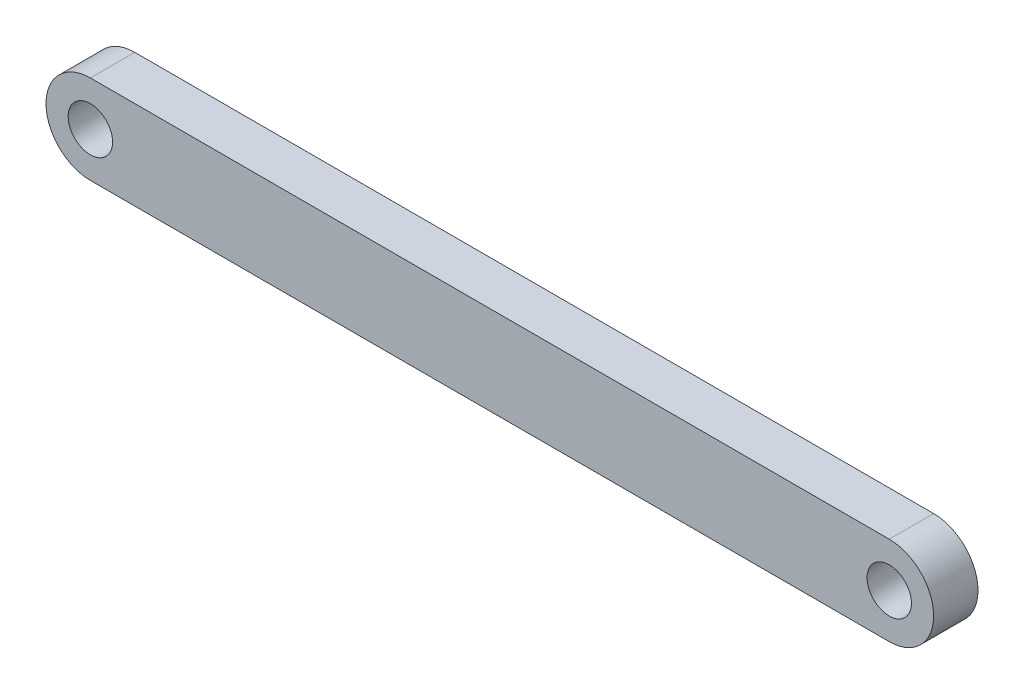
SolidWorks part; units mm, degrees
ref_plane "Alzado" through (0, 0, 0) normal (0, 0, 1) x (1, 0, 0)
ref_plane "Planta" through (0, 0, 0) normal (0, 1, 0) x (1, 0, 0)
ref_plane "Vista lateral" through (0, 0, 0) normal (1, 0, 0) x (0, 0, -1)
sketch "Croquis1" plane through (0, 0, 0) normal (0, 0, 1) x (1, 0, 0)
  line L0 (0, 0) -> (36, 0) construction
  line L1 (0, 2) -> (36, 2)
  line L2 (0, -2) -> (36, -2)
  arc A0 (0, 2) -> (0, -2) centre (0, 0) ccw
  arc A1 (36, -2) -> (36, 2) centre (36, 0) ccw
  circle A2 centre (0, 0) radius 1
  circle A3 centre (36, 0) radius 1
  point P3 (18, 0)
  point P8 (-2, 0)
  point P9 (38, 0)
  dimension "D2" = 2
  dimension "D3" = 2
  dimension "D4" = 2
  dimension "D1" = 40
extrude "Saliente-Extruir1" add sketch "Croquis1" along normal blind 2
